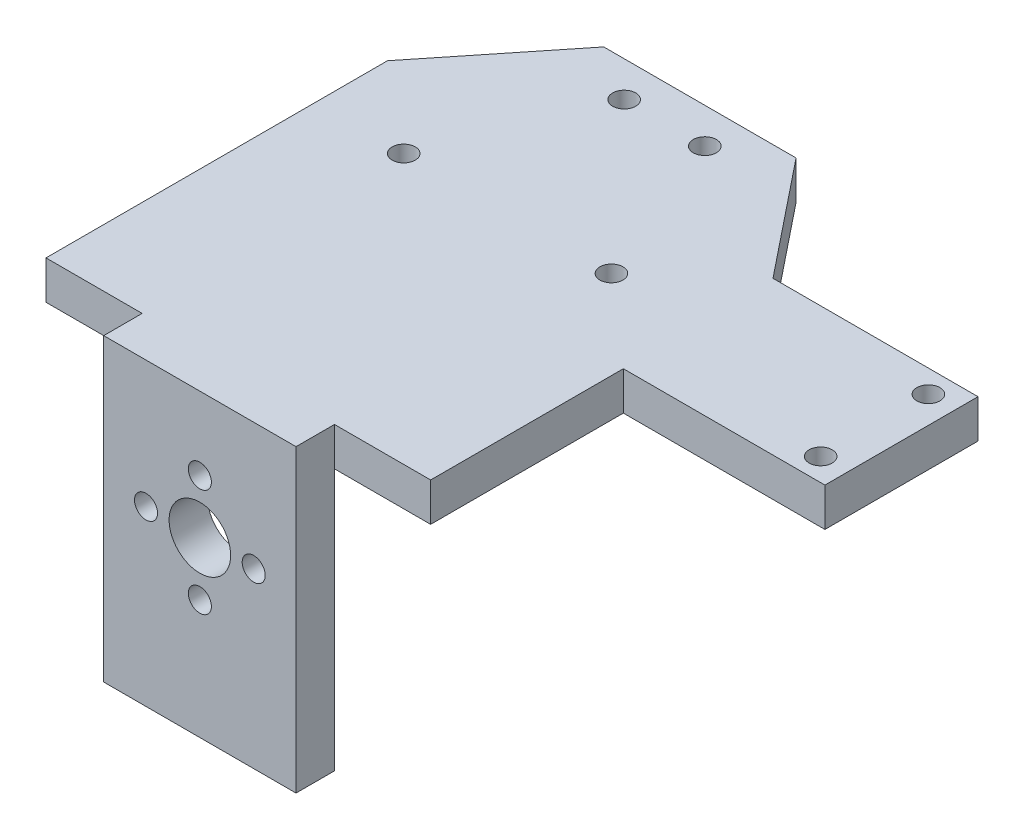
SolidWorks part; units mm, degrees
material "아크릴(내충격성)"
ref_plane "정면" through (0, 0, 0) normal (0, 0, 1) x (1, 0, 0)
ref_plane "윗면" through (0, 0, 0) normal (0, 1, 0) x (1, 0, 0)
ref_plane "우측면" through (0, 0, 0) normal (1, 0, 0) x (0, 0, -1)
sketch "스케치1" plane through (0, 0, 0) normal (0, 1, 0) x (1, 0, 0)
  line L0 (0, 21.0277) -> (0, -25.0991) construction
  line L1 (-25, 30) -> (25, 30)
  line L2 (-25, 30) -> (-25, -30)
  line L3 (-25, -30) -> (25, -30)
  line L4 (25, 30) -> (25, -30)
  line L5 (-25, 30) -> (25, -30) construction
  line L6 (-25, -30) -> (25, 30) construction
  line L7 (-25, 14.3875) -> (-12.5, 30)
  line L8 (12.5, 30) -> (25, 14.3875)
  circle A0 centre (-13.5, 5) radius 1.5
  circle A1 centre (13.5, 5) radius 1.5
  circle A2 centre (-5.24, 25.4) radius 1.5
  circle A3 centre (5.24, 25.4) radius 1.5
  point P0 (0, 0)
  dimension "D3" = 3
  dimension "D4" = 3
  dimension "D6" = 3
  dimension "D1" = 60
  dimension "D2" = 50
  dimension "D5" = 27
  dimension "D7" = 8.26
  dimension "D8" = 20.4
  dimension "D9" = 4.6
  dimension "D10" = 25
  dimension "D11" = 20
extrude "보스-돌출1" add sketch "스케치1" along normal blind 5 contours L8 L1 L7 L2 L3 L4 A3 A2 A1 A0
sketch "스케치2" plane through (0, 0, 30) normal (0, 0, 1) x (1, 0, 0)
  line L3 (-12.5, -34) -> (12.5, -34)
  line L4 (-12.5, -34) -> (-12.5, 5)
  line L5 (-25, 5) -> (25, 5) construction
  line L6 (-12.5, 5) -> (12.5, 5)
  line L7 (12.5, 5) -> (12.5, -34)
  circle A12 centre (0, -4.5) radius 1.5
  circle A13 centre (0, -11.5) radius 4
  circle A14 centre (7, -11.5) radius 1.5
  circle A15 centre (0, -11.5) radius 4
  circle A16 centre (0, -18.5) radius 1.5
  circle A17 centre (0, -11.5) radius 4
  circle A18 centre (-7, -11.5) radius 1.5
  circle A19 centre (0, -11.5) radius 4
  point P20 (0, -11.5)
  line M18 (-25, 0) -> (25, 0)
  line M20 (25, 5) -> (-25, 5)
  dimension "D1" = 3
  dimension "D2" = 7
  dimension "D4" = 8
  dimension "D3" = 4
extrude "보스-돌출2" add sketch "스케치2" along normal blind 5 contours L7 L4 L3 A18 A16 A14 A13 A12 M18 | L7 L4 M20 M18
sketch "스케치3" plane through (0, 5, 0) normal (0, 1, 0) x (1, 0, 0)
  line L1 (51.2, 14.95) -> (51.2, -4.95)
  line L2 (51.2, -4.95) -> (25, -4.95)
  line L3 (25, 14.3875) -> (25, -30) construction
  line L6 (51.2, 14.95) -> (24.5496, 14.95)
  line L7 (25, 14.3875) -> (25, -4.95)
  line L8 (12.5, 30) -> (25, 14.3875) construction
  line L9 (24.5496, 14.95) -> (25, 14.3875)
  circle A0 centre (47.7, -2) radius 1.5
  circle A1 centre (47.7, 12) radius 1.5
  dimension "D1" = 3
  dimension "D2" = 19.9
extrude "보스-돌출3" add sketch "스케치3" against normal blind 5
